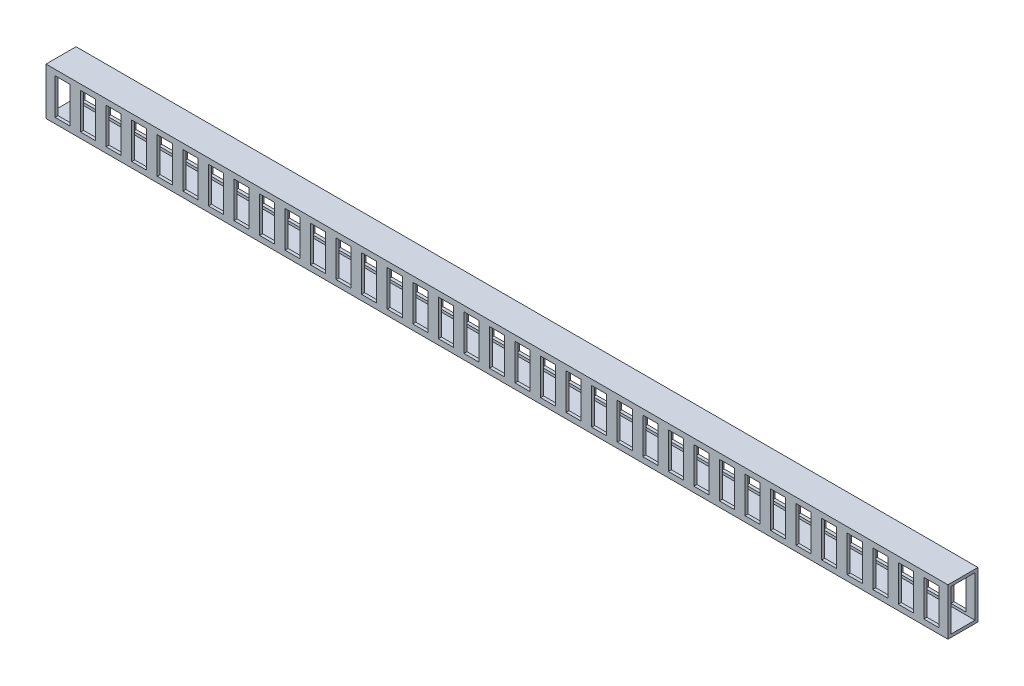
SolidWorks part; units mm, degrees
ref_plane "Front Plane" through (0, 0, 0) normal (0, 0, 1) x (1, 0, 0)
ref_plane "Top Plane" through (0, 0, 0) normal (0, 1, 0) x (1, 0, 0)
ref_plane "Right Plane" through (0, 0, 0) normal (1, 0, 0) x (0, 0, -1)
sketch "Sketch2" plane through (0, 0, 0) normal (1, 0, 0) x (0, 0, -1)
  line L1 (0, 0) -> (25.4, 0)
  line L2 (0, 0) -> (0, 39.878)
  line L3 (0, 39.878) -> (25.4, 39.878)
  line L4 (25.4, 0) -> (25.4, 39.878)
  dimension "D1" = 25.4
  dimension "D2" = 39.878
extrude "Boss-Extrude1" add sketch "Sketch2" along normal blind 762
sketch "Sketch3" plane through (762, 0, 0) normal (1, 0, 0) x (0, 0, -1)
  line L8 (2.54, 37.338) -> (2.54, 2.54)
  line L9 (2.54, 2.54) -> (22.86, 2.54)
  line L10 (22.86, 2.54) -> (22.86, 37.338)
  line L11 (22.86, 37.338) -> (2.54, 37.338)
  line L12 (2.54, 37.338) -> (2.54, 2.54)
  line L13 (2.54, 2.54) -> (22.86, 2.54)
  line L14 (22.86, 2.54) -> (22.86, 37.338)
  line L15 (22.86, 37.338) -> (2.54, 37.338)
  dimension "D1" = 2.54
extrude "Cut-Extrude1" cut sketch "Sketch3" against normal through all
sketch "Sketch4" plane through (0, 0, -25.4) normal (0, 0, -1) x (-1, 0, 0)
  line L1 (-754.38, 35.179) -> (-741.68, 35.179)
  line L2 (-754.38, 35.179) -> (-754.38, 4.699)
  line L3 (-754.38, 4.699) -> (-741.68, 4.699)
  line L4 (-741.68, 35.179) -> (-741.68, 4.699)
  line L5 (-762, 0) -> (-762, 39.878) construction
  line L6 (-732.79, 35.179) -> (-732.79, 4.699)
  line L7 (-732.79, 35.179) -> (-720.09, 35.179)
  line L8 (-720.09, 35.179) -> (-720.09, 4.699)
  line L9 (-732.79, 4.699) -> (-720.09, 4.699)
  line L10 (-711.2, 35.179) -> (-711.2, 4.699)
  line L11 (-711.2, 35.179) -> (-698.5, 35.179)
  line L12 (-698.5, 35.179) -> (-698.5, 4.699)
  line L13 (-711.2, 4.699) -> (-698.5, 4.699)
  line L14 (-689.61, 35.179) -> (-689.61, 4.699)
  line L15 (-689.61, 35.179) -> (-676.91, 35.179)
  line L16 (-676.91, 35.179) -> (-676.91, 4.699)
  line L17 (-689.61, 4.699) -> (-676.91, 4.699)
  line L18 (-668.02, 35.179) -> (-668.02, 4.699)
  line L19 (-668.02, 35.179) -> (-655.32, 35.179)
  line L20 (-655.32, 35.179) -> (-655.32, 4.699)
  line L21 (-668.02, 4.699) -> (-655.32, 4.699)
  line L22 (-646.43, 35.179) -> (-646.43, 4.699)
  line L23 (-646.43, 35.179) -> (-633.73, 35.179)
  line L24 (-633.73, 35.179) -> (-633.73, 4.699)
  line L25 (-646.43, 4.699) -> (-633.73, 4.699)
  line L26 (-624.84, 35.179) -> (-624.84, 4.699)
  line L27 (-624.84, 35.179) -> (-612.14, 35.179)
  line L28 (-612.14, 35.179) -> (-612.14, 4.699)
  line L29 (-624.84, 4.699) -> (-612.14, 4.699)
  line L30 (-603.25, 35.179) -> (-603.25, 4.699)
  line L31 (-603.25, 35.179) -> (-590.55, 35.179)
  line L32 (-590.55, 35.179) -> (-590.55, 4.699)
  line L33 (-603.25, 4.699) -> (-590.55, 4.699)
  line L34 (-581.66, 35.179) -> (-581.66, 4.699)
  line L35 (-581.66, 35.179) -> (-568.96, 35.179)
  line L36 (-568.96, 35.179) -> (-568.96, 4.699)
  line L37 (-581.66, 4.699) -> (-568.96, 4.699)
  line L38 (-560.07, 35.179) -> (-560.07, 4.699)
  line L39 (-560.07, 35.179) -> (-547.37, 35.179)
  line L40 (-547.37, 35.179) -> (-547.37, 4.699)
  line L41 (-560.07, 4.699) -> (-547.37, 4.699)
  line L42 (-538.48, 35.179) -> (-538.48, 4.699)
  line L43 (-538.48, 35.179) -> (-525.78, 35.179)
  line L44 (-525.78, 35.179) -> (-525.78, 4.699)
  line L45 (-538.48, 4.699) -> (-525.78, 4.699)
  line L46 (-516.89, 35.179) -> (-516.89, 4.699)
  line L47 (-516.89, 35.179) -> (-504.19, 35.179)
  line L48 (-504.19, 35.179) -> (-504.19, 4.699)
  line L49 (-516.89, 4.699) -> (-504.19, 4.699)
  line L50 (-495.3, 35.179) -> (-495.3, 4.699)
  line L51 (-495.3, 35.179) -> (-482.6, 35.179)
  line L52 (-482.6, 35.179) -> (-482.6, 4.699)
  line L53 (-495.3, 4.699) -> (-482.6, 4.699)
  line L54 (-473.71, 35.179) -> (-473.71, 4.699)
  line L55 (-473.71, 35.179) -> (-461.01, 35.179)
  line L56 (-461.01, 35.179) -> (-461.01, 4.699)
  line L57 (-473.71, 4.699) -> (-461.01, 4.699)
  line L58 (-452.12, 35.179) -> (-452.12, 4.699)
  line L59 (-452.12, 35.179) -> (-439.42, 35.179)
  line L60 (-439.42, 35.179) -> (-439.42, 4.699)
  line L61 (-452.12, 4.699) -> (-439.42, 4.699)
  line L62 (-430.53, 35.179) -> (-430.53, 4.699)
  line L63 (-430.53, 35.179) -> (-417.83, 35.179)
  line L64 (-417.83, 35.179) -> (-417.83, 4.699)
  line L65 (-430.53, 4.699) -> (-417.83, 4.699)
  line L66 (-408.94, 35.179) -> (-408.94, 4.699)
  line L67 (-408.94, 35.179) -> (-396.24, 35.179)
  line L68 (-396.24, 35.179) -> (-396.24, 4.699)
  line L69 (-408.94, 4.699) -> (-396.24, 4.699)
  line L70 (-387.35, 35.179) -> (-387.35, 4.699)
  line L71 (-387.35, 35.179) -> (-374.65, 35.179)
  line L72 (-374.65, 35.179) -> (-374.65, 4.699)
  line L73 (-387.35, 4.699) -> (-374.65, 4.699)
  line L74 (-365.76, 35.179) -> (-365.76, 4.699)
  line L75 (-365.76, 35.179) -> (-353.06, 35.179)
  line L76 (-353.06, 35.179) -> (-353.06, 4.699)
  line L77 (-365.76, 4.699) -> (-353.06, 4.699)
  line L78 (-344.17, 35.179) -> (-344.17, 4.699)
  line L79 (-344.17, 35.179) -> (-331.47, 35.179)
  line L80 (-331.47, 35.179) -> (-331.47, 4.699)
  line L81 (-344.17, 4.699) -> (-331.47, 4.699)
  line L82 (-322.58, 35.179) -> (-322.58, 4.699)
  line L83 (-322.58, 35.179) -> (-309.88, 35.179)
  line L84 (-309.88, 35.179) -> (-309.88, 4.699)
  line L85 (-322.58, 4.699) -> (-309.88, 4.699)
  line L86 (-300.99, 35.179) -> (-300.99, 4.699)
  line L87 (-300.99, 35.179) -> (-288.29, 35.179)
  line L88 (-288.29, 35.179) -> (-288.29, 4.699)
  line L89 (-300.99, 4.699) -> (-288.29, 4.699)
  line L90 (-279.4, 35.179) -> (-279.4, 4.699)
  line L91 (-279.4, 35.179) -> (-266.7, 35.179)
  line L92 (-266.7, 35.179) -> (-266.7, 4.699)
  line L93 (-279.4, 4.699) -> (-266.7, 4.699)
  line L94 (-257.81, 35.179) -> (-257.81, 4.699)
  line L95 (-257.81, 35.179) -> (-245.11, 35.179)
  line L96 (-245.11, 35.179) -> (-245.11, 4.699)
  line L97 (-257.81, 4.699) -> (-245.11, 4.699)
  line L98 (-236.22, 35.179) -> (-236.22, 4.699)
  line L99 (-236.22, 35.179) -> (-223.52, 35.179)
  line L100 (-223.52, 35.179) -> (-223.52, 4.699)
  line L101 (-236.22, 4.699) -> (-223.52, 4.699)
  line L102 (-214.63, 35.179) -> (-214.63, 4.699)
  line L103 (-214.63, 35.179) -> (-201.93, 35.179)
  line L104 (-201.93, 35.179) -> (-201.93, 4.699)
  line L105 (-214.63, 4.699) -> (-201.93, 4.699)
  line L106 (-193.04, 35.179) -> (-193.04, 4.699)
  line L107 (-193.04, 35.179) -> (-180.34, 35.179)
  line L108 (-180.34, 35.179) -> (-180.34, 4.699)
  line L109 (-193.04, 4.699) -> (-180.34, 4.699)
  line L110 (-171.45, 35.179) -> (-171.45, 4.699)
  line L111 (-171.45, 35.179) -> (-158.75, 35.179)
  line L112 (-158.75, 35.179) -> (-158.75, 4.699)
  line L113 (-171.45, 4.699) -> (-158.75, 4.699)
  line L114 (-149.86, 35.179) -> (-149.86, 4.699)
  line L115 (-149.86, 35.179) -> (-137.16, 35.179)
  line L116 (-137.16, 35.179) -> (-137.16, 4.699)
  line L117 (-149.86, 4.699) -> (-137.16, 4.699)
  line L118 (-128.27, 35.179) -> (-128.27, 4.699)
  line L119 (-128.27, 35.179) -> (-115.57, 35.179)
  line L120 (-115.57, 35.179) -> (-115.57, 4.699)
  line L121 (-128.27, 4.699) -> (-115.57, 4.699)
  line L122 (-106.68, 35.179) -> (-106.68, 4.699)
  line L123 (-106.68, 35.179) -> (-93.98, 35.179)
  line L124 (-93.98, 35.179) -> (-93.98, 4.699)
  line L125 (-106.68, 4.699) -> (-93.98, 4.699)
  line L126 (-85.09, 35.179) -> (-85.09, 4.699)
  line L127 (-85.09, 35.179) -> (-72.39, 35.179)
  line L128 (-72.39, 35.179) -> (-72.39, 4.699)
  line L129 (-85.09, 4.699) -> (-72.39, 4.699)
  line L130 (-63.5, 35.179) -> (-63.5, 4.699)
  line L131 (-63.5, 35.179) -> (-50.8, 35.179)
  line L132 (-50.8, 35.179) -> (-50.8, 4.699)
  line L133 (-63.5, 4.699) -> (-50.8, 4.699)
  line L134 (-41.91, 35.179) -> (-41.91, 4.699)
  line L135 (-41.91, 35.179) -> (-29.21, 35.179)
  line L136 (-29.21, 35.179) -> (-29.21, 4.699)
  line L137 (-41.91, 4.699) -> (-29.21, 4.699)
  line L138 (-20.32, 35.179) -> (-20.32, 4.699)
  line L139 (-20.32, 35.179) -> (-7.62, 35.179)
  line L140 (-7.62, 35.179) -> (-7.62, 4.699)
  line L141 (-20.32, 4.699) -> (-7.62, 4.699)
  point P4 (-754.38, 19.939)
  point P7 (-762, 19.939)
  dimension "D1" = 30.48
  dimension "D2" = 12.7
  dimension "D3" = 7.62
  dimension "D5" = 8.89
  dimension "D4" = 35
extrude "Cut-Extrude2" cut sketch "Sketch4" against normal through all
